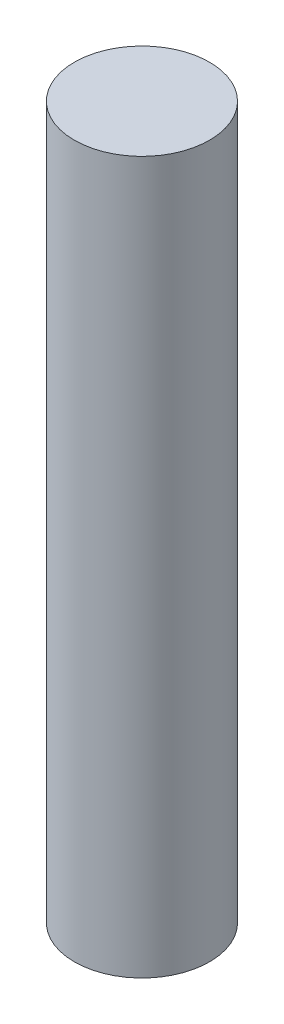
SolidWorks part; units mm, degrees
ref_plane "Front Plane" through (0, 0, 0) normal (0, 0, 1) x (1, 0, 0)
ref_plane "Top Plane" through (0, 0, 0) normal (0, 1, 0) x (1, 0, 0)
ref_plane "Right Plane" through (0, 0, 0) normal (1, 0, 0) x (0, 0, -1)
sketch "Sketch2" plane through (0, 0, 0) normal (0, 1, 0) x (1, 0, 0)
  circle A0 centre (0, 0) radius 1.9
  dimension "D1" = 3.8
extrude "Boss-Extrude1" add sketch "Sketch2" along normal blind 20
